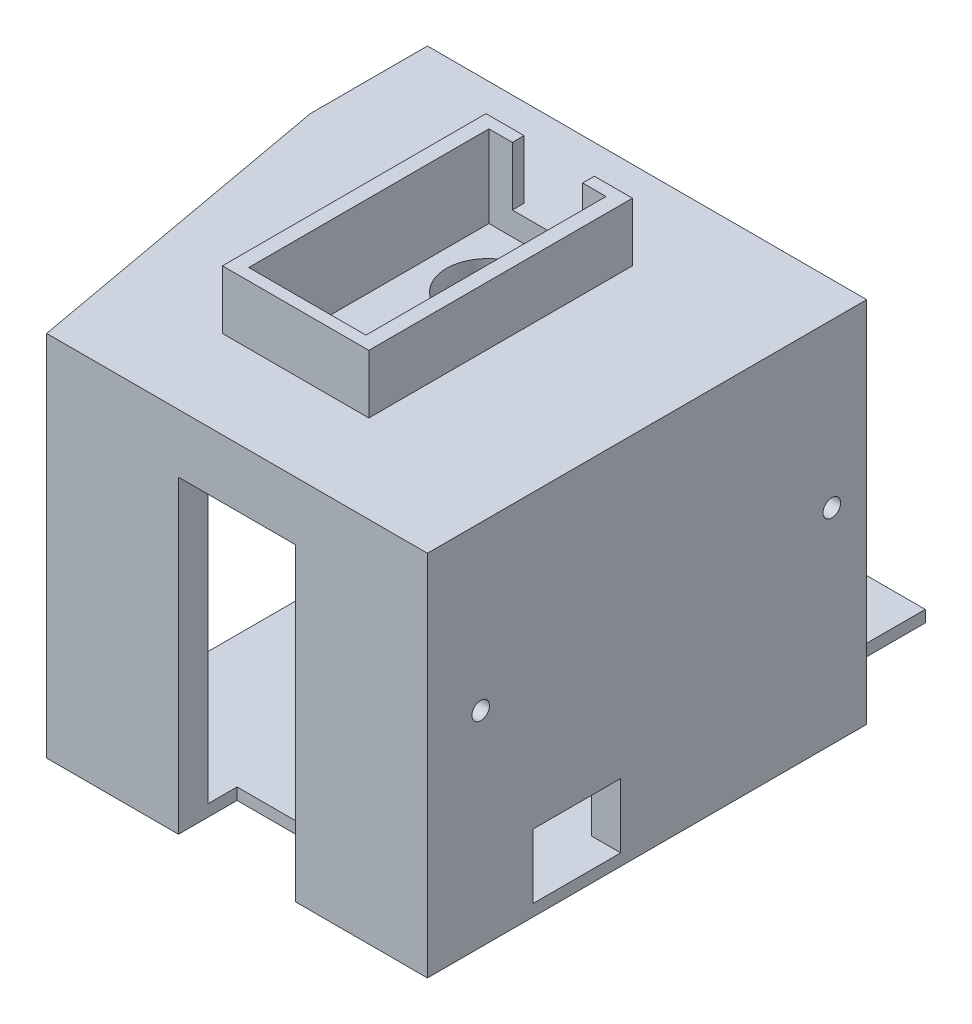
SolidWorks part; units mm, degrees
ref_plane "Front Plane" through (0, 0, 0) normal (0, 0, 1) x (1, 0, 0)
ref_plane "Top Plane" through (0, 0, 0) normal (0, 1, 0) x (1, 0, 0)
ref_plane "Right Plane" through (0, 0, 0) normal (1, 0, 0) x (0, 0, -1)
sketch "Sketch1" plane through (0, 0, 0) normal (0, 1, 0) x (1, 0, 0)
  line L1 (0, 0) -> (55, 0)
  line L2 (0, 0) -> (0, 65)
  line L3 (0, 65) -> (55, 65)
  line L4 (55, 0) -> (55, 65)
  dimension "D1" = 55
  dimension "D2" = 65
extrude "Base" add sketch "Sketch1" along normal blind 2
sketch "Sketch2" plane through (0, 2, 0) normal (0, 1, 0) x (1, 0, 0)
  line L0 (0, 0) -> (55, 0) construction
  line L2 (55, 65) -> (0, 65) construction
  circle A0 centre (3, 3.5) radius 1.2
  circle A1 centre (52, 3.5) radius 1.2
  circle A2 centre (3, 61.5) radius 1.2
  circle A3 centre (52, 61.5) radius 1.2
  point P12 (27.5, 0)
  dimension "D1" = 2.4
  dimension "D2" = 24.5
  dimension "D3" = 24.5
  dimension "D4" = 58
  dimension "D5" = 3.5
extrude "PiMountScrewHoles" cut sketch "Sketch2" against normal up to surface (2 mm away) up to face at (27.5, 0, -32.5)
sketch "Sketch3" plane through (0, 0, 0) normal (-1, 0, 0) x (0, 0, 1)
  line L0 (-65, 0) -> (0, 0) construction
  line L1 (-65, 2) -> (-45, 2)
  line L2 (-65, 2) -> (-65, 0)
  line L3 (-65, 0) -> (-45, 0)
  line L4 (-45, 2) -> (-45, 0)
  dimension "D1" = 20
extrude "PlateLegExt-1" add sketch "Sketch3" along normal blind 10
sketch "Sketch19" plane through (0, 0, -65) normal (0, 0, -1) x (-1, 0, 0)
  line L1 (-55, 2) -> (0, 2)
  line L2 (-55, 2) -> (-55, 0)
  line L3 (-55, 0) -> (0, 0)
  line L4 (0, 2) -> (0, 0)
extrude "PiFrontBase" add sketch "Sketch19" along normal blind 20
sketch "Sketch21" plane through (55, 0, 0) normal (1, 0, 0) x (0, 0, -1)
  line L0 (0, 0) -> (85, 0) construction
  line L1 (0, 2) -> (65, 2)
  line L2 (0, 2) -> (0, 0)
  line L3 (0, 0) -> (65, 0)
  line L4 (65, 2) -> (65, 0)
extrude "BatteryWall-Ext" add sketch "Sketch21" along normal blind 10
sketch "Sketch22" plane through (0, 0, 0) normal (0, 0, 1) x (1, 0, 0)
  line L0 (0, 0) -> (65, 0) construction
  line L1 (0, 2) -> (22.5, 2)
  line L2 (0, 2) -> (0, 0)
  line L3 (0, 0) -> (22.5, 0)
  line L4 (22.5, 2) -> (22.5, 0)
  line L6 (42.5, 2) -> (55, 2)
  line L7 (42.5, 2) -> (42.5, 0)
  line L8 (42.5, 0) -> (55, 0)
  line L11 (0, 2) -> (65, 2) construction
  line L12 (55, 2) -> (55, 0)
  line L13 (55, 0) -> (55, 2) construction
  point P16 (32.5, 0)
  dimension "D1" = 10
  dimension "D2" = 20
extrude "PlateLegExt-2" add sketch "Sketch22" along normal blind 10
sketch "Sketch30" plane through (55, 0, 0) normal (1, 0, 0) x (0, 0, -1)
  line L1 (-10, 2) -> (0, 2)
  line L2 (-10, 2) -> (-10, 0)
  line L3 (-10, 0) -> (0, 0)
  line L4 (0, 2) -> (0, 0)
extrude "CornerExtension" add sketch "Sketch30" along normal up to vertex (10 mm away) up to point (65, 0, 0)
sketch "Sketch23" plane through (0, 2, 0) normal (0, 1, 0) x (1, 0, 0)
  line L0 (65, 65) -> (55, 65) construction
  line L2 (22.5, -5) -> (0, -5)
  line L3 (22.5, -5) -> (22.5, -10)
  line L4 (-5, 65) -> (-10, 65)
  line L8 (60, 65) -> (65, 65)
  line L9 (60, 65) -> (60, -5)
  line L11 (65, 65) -> (65, -10)
  line L14 (-5, 65) -> (-5, 45)
  line L15 (-5, 45) -> (-10, 45)
  line L16 (-10, 65) -> (-10, 45)
  line L21 (22.5, -10) -> (0, -10)
  line L22 (0, -5) -> (0, -10)
  line L23 (22.5, -10) -> (22.5, 0) construction
  line L24 (0, 65) -> (-10, 65) construction
  line L25 (42.5, -10) -> (42.5, 0) construction
  line L26 (42.5, -10) -> (65, -10)
  line L27 (42.5, -10) -> (42.5, -5)
  line L30 (65, 65) -> (65, -10) construction
  line L31 (65, -10) -> (42.5, -10) construction
  line L32 (42.5, -5) -> (60, -5)
extrude "PlateLegs" add sketch "Sketch23" along normal blind 50.8
sketch "Sketch29" plane through (65, 0, 0) normal (1, 0, 0) x (0, 0, -1)
  line L0 (-10, 0) -> (65, 0) construction
  circle A0 centre (59.045, 35) radius 1.5
  circle A1 centre (-0.905, 35) radius 1.5
  point P8 (27.5, 0)
  dimension "D1" = 3
  dimension "D2" = 59.95
  dimension "D3" = 31.545
  dimension "D4" = 35
extrude "Battery-ScrewHoles" cut sketch "Sketch29" against normal up to surface (5 mm away) up to face at (60, 27.4, -30)
sketch "Sketch24" plane through (0, 52.8, 0) normal (0, 1, 0) x (1, 0, 0)
  line L7 (0, -10) -> (65, -10)
  line L8 (42.5, -10) -> (65, -10) construction
  line L9 (65, -10) -> (65, 65)
  line L10 (65, 65) -> (-10, 65)
  line L11 (-10, 65) -> (-10, 45)
  line L12 (-10, 45) -> (0, -10)
extrude "RotatorPlate" add sketch "Sketch24" along normal blind 10
sketch "Sketch25" plane through (0, 62.8, 0) normal (0, 1, 0) x (1, 0, 0)
  line L2 (37.5, 7) -> (37.5, 48)
  line L4 (17.5, 7) -> (17.5, 48)
  line L7 (37.5, 48) -> (17.5, 48)
  line L8 (17.5, 7) -> (37.5, 7)
  line L9 (65, -10) -> (65, 65) construction
  line L11 (65, 65) -> (-10, 65) construction
  point P8 (27.5, 65)
  point P9 (65, 27.5)
  point P10 (37.5, 27.5)
  point P11 (27.5, 48)
  dimension "D1" = 41
  dimension "D2" = 20
extrude "Inset-Servo" cut sketch "Sketch25" against normal blind 4
sketch "Sketch26" plane through (0, 58.8, 0) normal (0, 1, 0) x (1, 0, 0)
  line L3 (37.5, 48) -> (17.5, 48) construction
  circle A0 centre (27.5, 37.75) radius 1.5
  point P8 (27.5, 48)
  dimension "D1" = 3
  dimension "D2" = 10.25
extrude "Hole-ServoScrew" cut sketch "Sketch26" against normal up to surface (6 mm away) up to face at (20.9091, 52.8, -15.4545)
sketch "Sketch27" plane through (0, 58.8, 0) normal (0, 1, 0) x (1, 0, 0)
  circle A0 centre (27.5, 37.75) radius 7
  circle A1 centre (27.5, 37.75) radius 1.5 construction
  dimension "D1" = 14
extrude "Inset-ServoAxle" cut sketch "Sketch27" against normal blind 5.8
sketch "Sketch28" plane through (0, 62.8, 0) normal (0, 1, 0) x (1, 0, 0)
  line L0 (37.5, 48) -> (33.5, 48)
  line L1 (37.5, 7) -> (17.5, 7)
  line L2 (37.5, 7) -> (37.5, 48)
  line L4 (17.5, 7) -> (17.5, 48)
  line L5 (40, 5) -> (15, 5)
  line L6 (40, 5) -> (40, 50)
  line L8 (15, 5) -> (15, 50)
  line L9 (37.5, 48) -> (17.5, 48) construction
  line L10 (17.5, 48) -> (21.5, 48)
  line L11 (37.5, 7) -> (37.5, 48) construction
  line L12 (33.5, 48) -> (33.5, 50)
  line L13 (33.5, 50) -> (40, 50)
  line L14 (21.5, 48) -> (21.5, 50)
  line L15 (21.5, 50) -> (15, 50)
  line L16 (37.5, 48) -> (17.5, 48) construction
  line L17 (17.5, 7) -> (37.5, 7) construction
  line L18 (17.5, 48) -> (17.5, 7) construction
  point P15 (27.5, 7)
  point P19 (27.5, 5)
  point P20 (40, 27.5)
  point P21 (37.5, 27.5)
  point P28 (27.5, 48)
  point P29 (21.5, 49)
  dimension "D1" = 6
  dimension "D2" = 12
  dimension "D3" = 45
  dimension "D4" = 25
extrude "RetainingWalls-Servo" add sketch "Sketch28" along normal blind 10
sketch "Sketch31" plane through (60, 0, 0) normal (-1, 0, 0) x (0, 0, 1)
  line L0 (-65, 2) -> (5, 2) construction
  line L1 (-23, 13) -> (-8, 13)
  line L2 (-23, 13) -> (-23, 2)
  line L3 (-23, 2) -> (-8, 2)
  line L4 (-8, 13) -> (-8, 2)
  line L5 (5, 52.8) -> (5, 2) construction
  dimension "D1" = 15
  dimension "D2" = 11
  dimension "D3" = 13
extrude "Power-Hole" cut sketch "Sketch31" against normal up to surface (5 mm away)
equation "\"PlateLegExtent\"= 10mm"
equation "\"D1@PlateLegExt-1\" = \"PlateLegExtent\""
equation "\"PlateLegHeight\"= 2in"
equation "\"D1@BatteryWall-Ext\" = \"PlateLegExtent\""
equation "\"D1@PlateLegExt-2\" = \"PlateLegExtent\""
equation "\"D1@PlateLegs\" = \"PlateLegHeight\""
